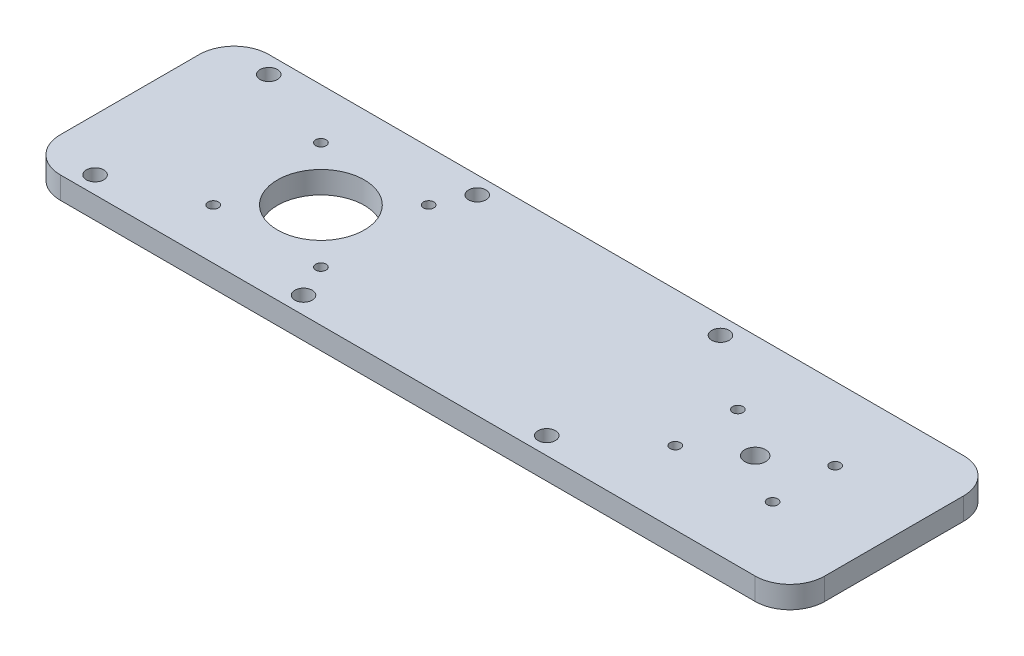
SolidWorks part; units mm, degrees
ref_plane "Front Plane" through (0, 0, 0) normal (0, 0, 1) x (1, 0, 0)
ref_plane "Top Plane" through (0, 0, 0) normal (0, 1, 0) x (1, 0, 0)
ref_plane "Right Plane" through (0, 0, 0) normal (1, 0, 0) x (0, 0, -1)
sketch "Sketch1" plane through (0, 0, 0) normal (0, 1, 0) x (1, 0, 0)
  line L0 (-55, 0) -> (0, 0) construction
  line L1 (-55, 30) -> (165, 30)
  line L2 (-55, 30) -> (-55, -30)
  line L3 (-55, -30) -> (165, -30)
  line L4 (165, 30) -> (165, -30)
  point P7 (125, 0)
  dimension "D1" = 60
  dimension "D2" = 55
  dimension "D3" = 125
  dimension "D4" = 40
extrude "Boss-Extrude1" add sketch "Sketch1" along normal blind 6.35
fillet "Fillet1" radius 10 4 edges at (-55, 3.175, 30) (-55, 3.175, -30) (165, 3.175, 30) (165, 3.175, -30)
hole_wizard "Ø3.0mm Dowel Hole1" positions "Sketch3" profile "Sketch5" hole size "Ø3.0" standard "DIN" end condition up to next
sketch "Sketch3" plane through (0, 6.35, 0) normal (0, 1, 0) x (1, 0, 0)
  point P0 (-15.5, 15.5)
  point P29 (15.5, 15.5)
  point P30 (15.5, -15.5)
  point P31 (-15.5, -15.5)
  dimension "D1" = 15.5
  dimension "D2" = 15.5
  dimension "D5" = 31
  dimension "D6" = 31
  dimension "D3" = 2
  dimension "D4" = 2
sketch "Sketch5" plane through (-15.5, 6.35, -15.5) normal (1, 0, 0) x (0, 0, 1)
  line L0 (0, 0) -> (0, 6.35)
  line L1 (0, 6.35) -> (1.5, 6.35)
  line L2 (1.5, 6.35) -> (1.5, 0)
  line L5 (1.5, 0) -> (0, 0)
  line L11 (0, -6.35) -> (0, 107.95) construction
  dimension "Thru Hole Dia." = 3
  dimension "Thru Hole Depth" = 6.35
sketch "Sketch6" plane through (0, 6.35, 0) normal (0, 1, 0) x (1, 0, 0)
  circle A0 centre (0, 0) radius 12.5
  dimension "D1" = 25
extrude "Cut-Extrude1" cut sketch "Sketch6" against normal through all
hole_wizard "Ø6.0mm Dowel Hole1" positions "Sketch7" profile "Sketch8" hole size "Ø6.0" standard "DIN" end condition up to next
sketch "Sketch7" plane through (0, 6.35, 0) normal (0, 1, 0) x (1, 0, 0)
  point P0 (125, 0)
  dimension "D1" = 125
sketch "Sketch8" plane through (125, 6.35, 0) normal (1, 0, 0) x (0, 0, 1)
  line L0 (0, 0) -> (0, 6.35)
  line L1 (0, 6.35) -> (3, 6.35)
  line L2 (3, 6.35) -> (3, 0)
  line L5 (3, 0) -> (0, 0)
  line L11 (0, -6.35) -> (0, 107.95) construction
  dimension "Thru Hole Dia." = 6
  dimension "Thru Hole Depth" = 6.35
hole_wizard "Ø3.0mm Dowel Hole2" positions "Sketch10" profile "Sketch11" hole size "Ø3.0" standard "ANSI Metric" end condition up to next
sketch "Sketch10" plane through (0, 0, 0) normal (0, -1, 0) x (-1, 0, 0)
  line L0 (-139, 9) -> (-111, 9) construction
  circle A0 centre (-125, 0) radius 3 construction
  point P0 (-139, 9)
  point P7 (-111, 9)
  point P8 (-111, -9)
  point P9 (-139, -9)
  dimension "D4" = 14
  dimension "D5" = 9
  dimension "D3" = 28
  dimension "D6" = 18
  dimension "D1" = 2
  dimension "D2" = 2
sketch "Sketch11" plane through (139, 0, -9) normal (1, 0, 0) x (0, 0, -1)
  line L0 (0, 0) -> (0, 6.35)
  line L1 (0, 6.35) -> (1.5, 6.35)
  line L2 (1.5, 6.35) -> (1.5, 0)
  line L5 (1.5, 0) -> (0, 0)
  line L11 (0, -6.35) -> (0, 107.95) construction
  dimension "Thru Hole Dia." = 3
  dimension "Thru Hole Depth" = 6.35
hole_wizard "Ø5.0mm Dowel Hole1" positions "Sketch12" profile "Sketch13" hole size "Ø5.0" standard "DIN" end condition through all
sketch "Sketch12" plane through (0, 6.35, 0) normal (0, 1, 0) x (1, 0, 0)
  line L0 (-45, -30) -> (155, -30) construction
  line L1 (20, -25) -> (90, -25) construction
  line L2 (-55, 0) -> (165, 0) construction
  line L3 (-55, 20) -> (-55, -20) construction
  line L4 (165, -20) -> (165, 20) construction
  line L5 (55, 30) -> (55, -30) construction
  line L6 (155, 30) -> (-45, 30) construction
  line L9 (55, -25) -> (20, -25) construction
  line L11 (55, 25) -> (90, 25) construction
  line L13 (55, 25) -> (20, 25) construction
  point P0 (20, -25)
  point P14 (90, -25)
  point P26 (90, 25)
  point P27 (20, 25)
  point P28 (-40, -25)
  point P31 (-40, 25)
  dimension "D1" = 5
  dimension "D4" = 70
  dimension "D5" = 15
  dimension "D3" = 2
sketch "Sketch13" plane through (20, 6.35, 25) normal (1, 0, 0) x (0, 0, 1)
  line L0 (0, 0) -> (0, 6.35)
  line L1 (0, 6.35) -> (2.5, 6.35)
  line L2 (2.5, 6.35) -> (2.5, 0)
  line L5 (2.5, 0) -> (0, 0)
  line L11 (0, -6.35) -> (0, 107.95) construction
  dimension "Thru Hole Dia." = 5
  dimension "Thru Hole Depth" = 6.35
equation "\"Pivot to Pivot Dist\" = 125"
equation "\"D3@Sketch1\"=\"Pivot to Pivot Dist\""
equation "\"D1@Sketch7\"=\"Pivot to Pivot Dist\""
